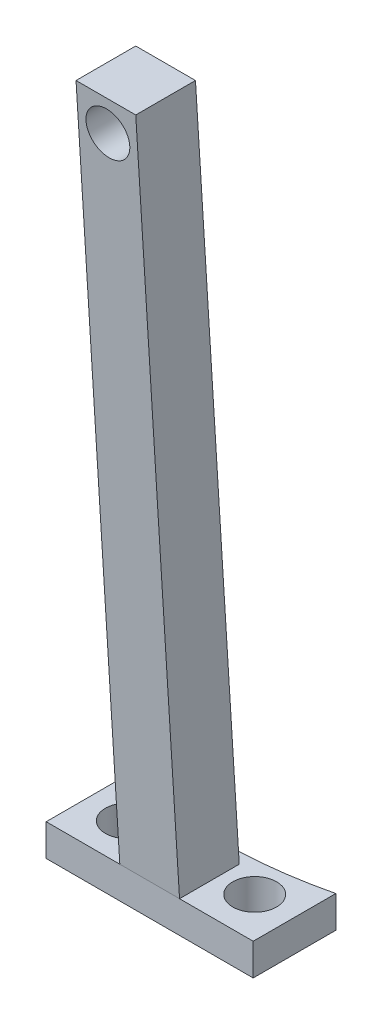
SolidWorks part; units mm, degrees
ref_plane "Front Plane" through (0, 0, 0) normal (0, 0, 1) x (1, 0, 0)
ref_plane "Top Plane" through (0, 0, 0) normal (0, 1, 0) x (1, 0, 0)
ref_plane "Right Plane" through (0, 0, 0) normal (1, 0, 0) x (0, 0, -1)
sketch "Sketch1" plane through (0, 0, 0) normal (0, 1, 0) x (1, 0, 0)
  line L0 (-6.5, 0) -> (6.5, 0)
  line L1 (-6.5, 0) -> (-6.5, 5.19)
  line L2 (6.5, 0) -> (6.5, 5.19)
  spline S0 degree 2 poles (-6.5, 5.19) (0, 3.63) (6.5, 5.19) knots 0 0 0 1 1 1
  point P4 (0, 0)
  dimension "D1" = 13
  dimension "D2" = 5.19
  dimension "D3" = 4.41
extrude "Boss-Extrude1" add sketch "Sketch1" along normal blind 2
sketch "Sketch2" plane through (0, 2, 0) normal (0, 1, 0) x (1, 0, 0)
  line L0 (-6.5, 2.595) -> (6.5, 2.595) construction
  line L1 (-6.5, 5.19) -> (-6.5, 0) construction
  line L2 (6.5, 0) -> (6.5, 5.19) construction
  circle A0 centre (-4, 2.595) radius 1.375
  circle A1 centre (4, 2.595) radius 1.375
  dimension "D3" = 2.75
  dimension "D1" = 2.5
  dimension "D2" = 2.5
extrude "Cut-Extrude1" cut sketch "Sketch2" against normal blind 2
sketch "Sketch4" plane through (0, 2, 0) normal (0, 1, 0) x (1, 0, 0)
  line L0 (-1.875, 3.75) -> (1.875, 3.75)
  line L1 (-1.875, 3.75) -> (-1.875, 0)
  line L2 (-6.5, 0) -> (6.5, 0) construction
  line L3 (-1.875, 0) -> (1.875, 0)
  line L4 (1.875, 0) -> (1.875, 3.75)
  point P2 (0, 3.75)
  dimension "D1" = 3.75
  dimension "D2" = 3.75
ref_plane "Plane1" through (0, 46, 0) normal (0, 1, 0) x (1, 0, 0)
sketch "Sketch6" plane through (0, 46, 0) normal (0, 1, 0) x (1, 0, 0)
  line L5 (-1.875, 1) -> (1.875, 1)
  line L6 (-1.875, 0) -> (1.875, 0) construction
  line L7 (-1.875, 1) -> (-1.875, -2.75)
  line L8 (-1.875, -2.75) -> (1.875, -2.75)
  line L9 (1.875, -2.75) -> (1.875, 1)
  line L10 (-1.875, 3.75) -> (-1.875, 0) construction
  line L11 (-1.875, 3.75) -> (1.875, 3.75) construction
  point P13 (0, 1)
  point P16 (0, 3.75)
  dimension "D1" = 1
loft "Loft2" add profiles "Sketch4", "Sketch6"
sketch "Sketch12" plane through (0, 0, 0) normal (0, 0, 1) x (1, 0, 0)
  line L0 (0, -1.1) -> (0, 1.1) construction
  line L1 (2.8603, 46) -> (-2.8603, 46) construction
  circle A0 centre (0, 44) radius 1.375
  dimension "D1" = 2.75
  dimension "D2" = 2
extrude "Cut-Extrude3" cut sketch "Sketch12" against normal through all both and the other way through all
sketch "Sketch8" plane through (0, 46, 0) normal (0, 1, 0) x (1, 0, 0)
  line L0 (-1.875, 1) -> (1.875, 1)
  line L1 (1.875, 1) -> (1.875, -9.75)
  line L2 (1.875, -9.75) -> (-1.875, -9.75)
  line L3 (-1.875, -9.75) -> (-1.875, 1)
  line L4 (-1.875, -2.75) -> (1.875, -2.75) construction
  dimension "D1" = 7
